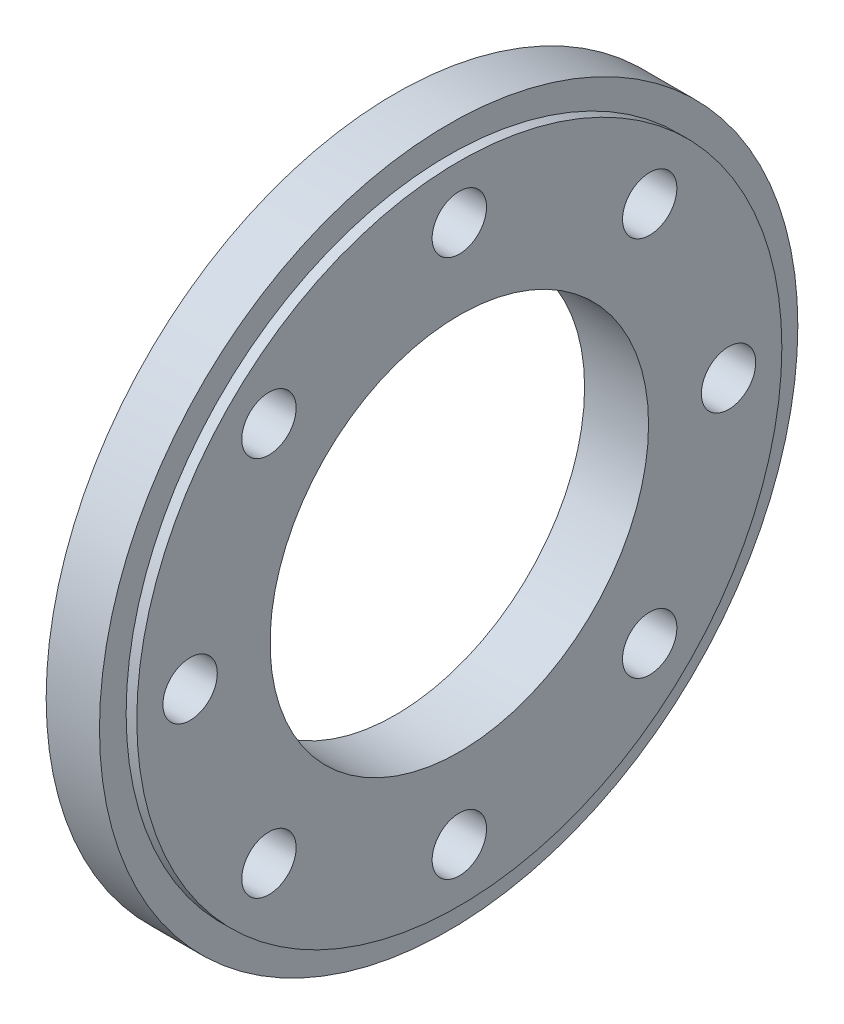
SolidWorks part; units mm, degrees
material "AISI 304"
ref_plane "Спереди" through (0, 0, 0) normal (0, 0, 1) x (1, 0, 0)
ref_plane "Сверху" through (0, 0, 0) normal (0, 1, 0) x (1, 0, 0)
ref_plane "Справа" through (0, 0, 0) normal (1, 0, 0) x (0, 0, -1)
other "Configuration Table"
sketch "Эскиз1" plane through (0, 0, 0) normal (1, 0, 0) x (0, 0, -1)
  line L0 (0, 0) -> (0, 50.5) construction
  circle A0 centre (0, 0) radius 35.5
  circle A1 centre (0, 0) radius 65.5
  circle A2 centre (0, 0) radius 50.5 construction
  circle A3 centre (0, 50.5) radius 5.1
  circle A4 centre (35.7089, 35.7089) radius 5.1
  circle A5 centre (50.5, 0) radius 5.1
  circle A6 centre (35.7089, -35.7089) radius 5.1
  circle A7 centre (0, -50.5) radius 5.1
  circle A8 centre (-35.7089, -35.7089) radius 5.1
  circle A9 centre (-50.5, 0) radius 5.1
  circle A10 centre (-35.7089, 35.7089) radius 5.1
  point P24 (0, 0)
  dimension "D1" = 71
  dimension "D4" = 10.2
  dimension "D2" = 15
  dimension "D3" = 15
  dimension "D5" = 8
extrude "Бобышка-Вытянуть1" add sketch "Эскиз1" along normal mid plane 12
sketch "Эскиз2" plane through (6, 0, 0) normal (1, 0, 0) x (0, 0, -1)
  circle A0 centre (0, 0) radius 65.5
  circle A1 centre (0, 0) radius 60.5
  dimension "D1" = 131
  dimension "D2" = 5
extrude "Вырез-Вытянуть1" cut sketch "Эскиз2" against normal blind 2
equation "\"D3@Эскиз1\"=\"D2@Эскиз1\""
